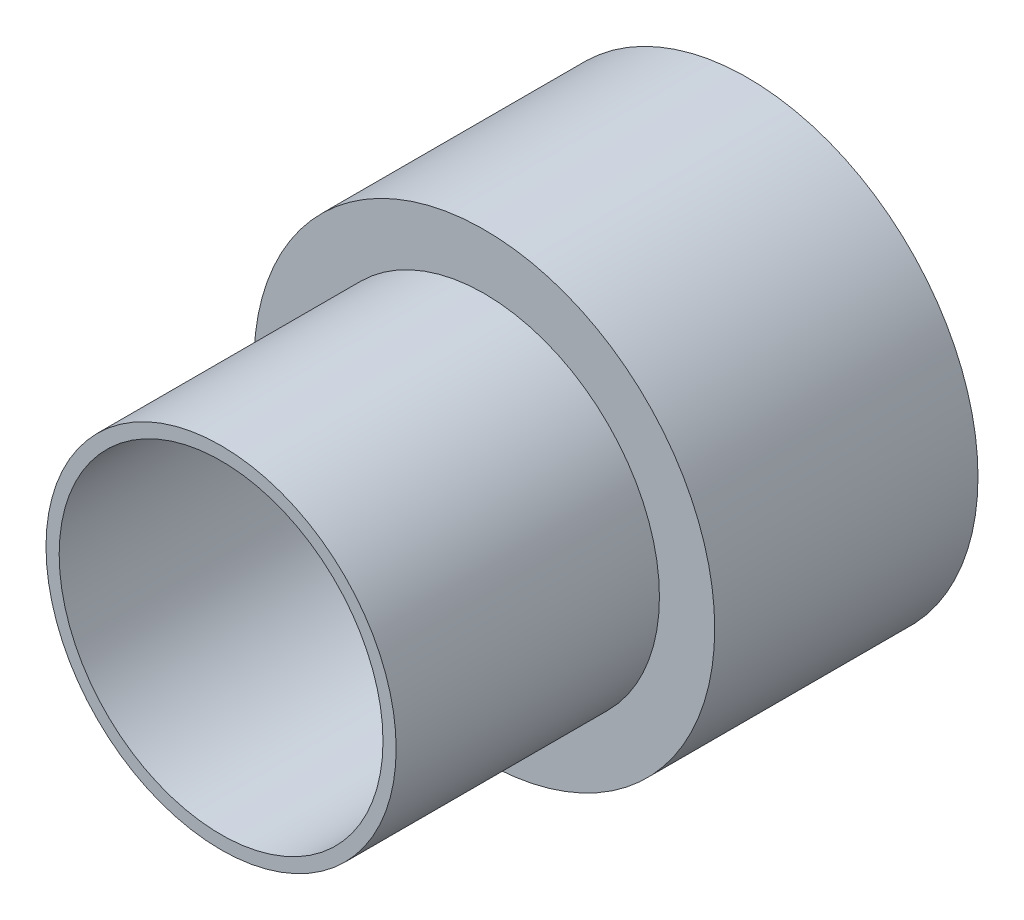
SolidWorks part; units mm, degrees
ref_plane "Front Plane" through (0, 0, 0) normal (0, 0, 1) x (1, 0, 0)
ref_plane "Top Plane" through (0, 0, 0) normal (0, 1, 0) x (1, 0, 0)
ref_plane "Right Plane" through (0, 0, 0) normal (1, 0, 0) x (0, 0, -1)
sketch "Sketch1" plane through (0, 0, 0) normal (0, 0, 1) x (1, 0, 0)
  circle A1 centre (0, 0) radius 22.225
  dimension "D1" = 44.45
extrude "Boss-Extrude1" add sketch "Sketch1" along normal blind 25.4
sketch "Sketch2" plane through (0, 0, 25.4) normal (0, 0, 1) x (1, 0, 0)
  circle A0 centre (0, 0) radius 16.891
  dimension "D1" = 33.782
extrude "Boss-Extrude2" add sketch "Sketch2" along normal blind 25.4
sketch "Sketch3" plane through (0, 0, 50.8) normal (0, 0, 1) x (1, 0, 0)
  circle A0 centre (0, 0) radius 15.621
  dimension "D1" = 31.242
extrude "Cut-Extrude1" cut sketch "Sketch3" against normal blind 50.8
sketch "Sketch4" plane through (0, 0, 0) normal (0, 0, -1) x (-1, 0, 0)
  circle A0 centre (0, 0) radius 19.685
  dimension "D1" = 39.37
extrude "Cut-Extrude2" cut sketch "Sketch4" against normal blind 22.225
